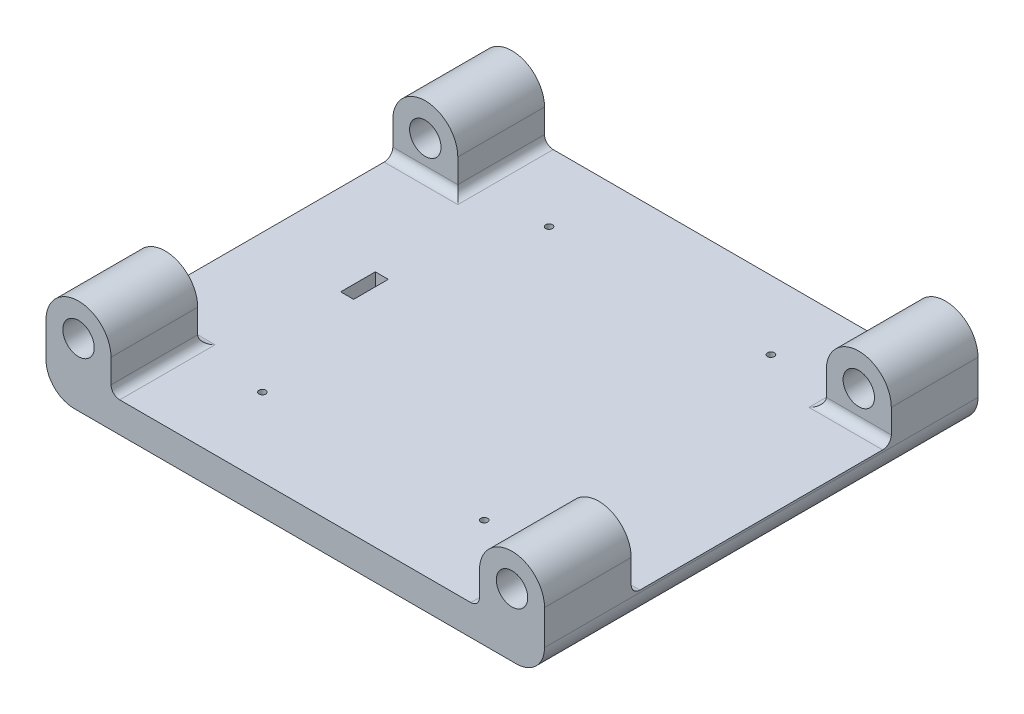
SolidWorks part; units mm, degrees
ref_plane "Front Plane" through (0, 0, 0) normal (0, 0, 1) x (1, 0, 0)
ref_plane "Top Plane" through (0, 0, 0) normal (0, 1, 0) x (1, 0, 0)
ref_plane "Right Plane" through (0, 0, 0) normal (1, 0, 0) x (0, 0, -1)
sketch "Sketch2" plane through (0, 0, 0) normal (0, 0, 1) x (1, 0, 0)
  line L0 (-25.6615, -36.6768) -> (-25.6615, -43.6618)
  line L1 (-23.1215, -46.2018) -> (79.7485, -46.2018)
  line L2 (-44.7115, -46.2018) -> (-44.7115, -46.8368)
  line L3 (-36.4565, -55.0918) -> (93.0835, -55.0918)
  line L4 (101.3385, -46.2018) -> (101.3385, -46.8368)
  line L5 (82.2885, -36.6768) -> (82.2885, -43.6618)
  line L6 (-44.7115, -36.6768) -> (-44.7115, -46.2018)
  line L7 (101.3385, -36.6768) -> (101.3385, -46.2018)
  line L8 (-35.1865, -36.6768) -> (91.8135, -36.6768) construction
  circle A0 centre (-35.1865, -36.6768) radius 4.6037
  circle A1 centre (91.8135, -36.6768) radius 4.6038
  arc A2 (-25.6615, -36.6768) -> (-44.7115, -36.6768) centre (-35.1865, -36.6768) ccw
  arc A3 (101.3385, -36.6768) -> (82.2885, -36.6768) centre (91.8135, -36.6768) ccw
  arc A4 (79.7485, -46.2018) -> (82.2885, -43.6618) centre (79.7485, -43.6618) ccw
  arc A5 (-23.1215, -46.2018) -> (-25.6615, -43.6618) centre (-23.1215, -43.6618) cw
  arc A6 (93.0835, -55.0918) -> (101.3385, -46.8368) centre (93.0835, -46.8368) ccw
  arc A7 (-36.4565, -55.0918) -> (-44.7115, -46.8368) centre (-36.4565, -46.8368) cw
  point P22 (-44.7115, -55.0918)
  dimension "D1" = 9.2075
  dimension "D2" = 9.2075
  dimension "D4" = 19.05
  dimension "D5" = 19.05
  dimension "D8" = 9.525
  dimension "D10" = 9.525
  dimension "D11" = 2.54
  dimension "D12" = 8.255
  dimension "D3" = 127
  dimension "D6" = 8.89
  dimension "D7" = 146.05
  dimension "D9" = 9.525
extrude "Boss-Extrude1" add sketch "Sketch2" against normal blind 127
sketch "Sketch3" plane through (101.3385, 0, 0) normal (1, 0, 0) x (0, 0, -1)
  line L1 (25.4, -46.2018) -> (101.6, -46.2018)
  line L2 (25.4, -46.2018) -> (25.4, -14.7274)
  line L3 (25.4, -14.7274) -> (101.6, -14.7274)
  line L4 (101.6, -46.2018) -> (101.6, -14.7274)
  line L5 (0, -27.1518) -> (0, -36.6768) construction
  line L6 (127, -27.1518) -> (0, -27.1518) construction
  dimension "D1" = 25.4
  dimension "D2" = 76.2
  dimension "D3" = 19.05
extrude "Cut-Extrude1" cut sketch "Sketch3" against normal blind 254
fillet "Fillet1" radius 2.54 2 edges at (-24.9175, -45.4579, -25.4) (-33.9165, -46.2018, -25.4)
fillet "Fillet2" radius 2.54 2 edges at (-33.9165, -46.2018, -101.6) (-24.9175, -45.4579, -101.6)
fillet "Fillet3" radius 2.54 2 edges at (81.5446, -45.4579, -101.6) (90.5435, -46.2018, -101.6)
fillet "Fillet4" radius 2.54 2 edges at (81.5446, -45.4579, -25.4) (90.5435, -46.2018, -25.4)
sketch "Sketch4" plane through (0, -46.2018, 0) normal (0, 1, 0) x (1, 0, 0)
  line L0 (-44.7115, 99.06) -> (-44.7115, 27.94) construction
  line L1 (101.3385, 27.94) -> (101.3385, 99.06) construction
  line L2 (79.7485, 0) -> (-23.1215, 0) construction
  line L3 (-4.1858, 106.86) -> (-4.1858, 22.86) construction
  line L4 (-18.1557, 69.9243) -> (-14.3457, 69.9243)
  line L5 (-18.1557, 69.9243) -> (-18.1557, 59.7643)
  line L6 (-18.1557, 59.7643) -> (-14.3457, 59.7643)
  line L7 (-14.3457, 69.9243) -> (-14.3457, 59.7643)
  circle A0 centre (-4.1858, 106.86) radius 1
  circle A1 centre (60.8142, 106.86) radius 1
  circle A2 centre (-4.1858, 22.86) radius 1
  circle A3 centre (60.8142, 22.86) radius 1
  point P18 (-14.3457, 64.8443)
  point P19 (-4.1858, 64.86)
  dimension "D1" = 2
  dimension "D2" = 2
  dimension "D3" = 2
  dimension "D4" = 2
  dimension "D5" = 84
  dimension "D6" = 65
  dimension "D7" = 40.5257
  dimension "D8" = 40.5243
  dimension "D9" = 22.86
  dimension "D10" = 10.16
  dimension "D11" = 3.81
  dimension "D12" = 10.16
  dimension "D13" = 65
  dimension "D14" = 84
extrude "Cut-Extrude2" cut sketch "Sketch4" against normal blind 254
